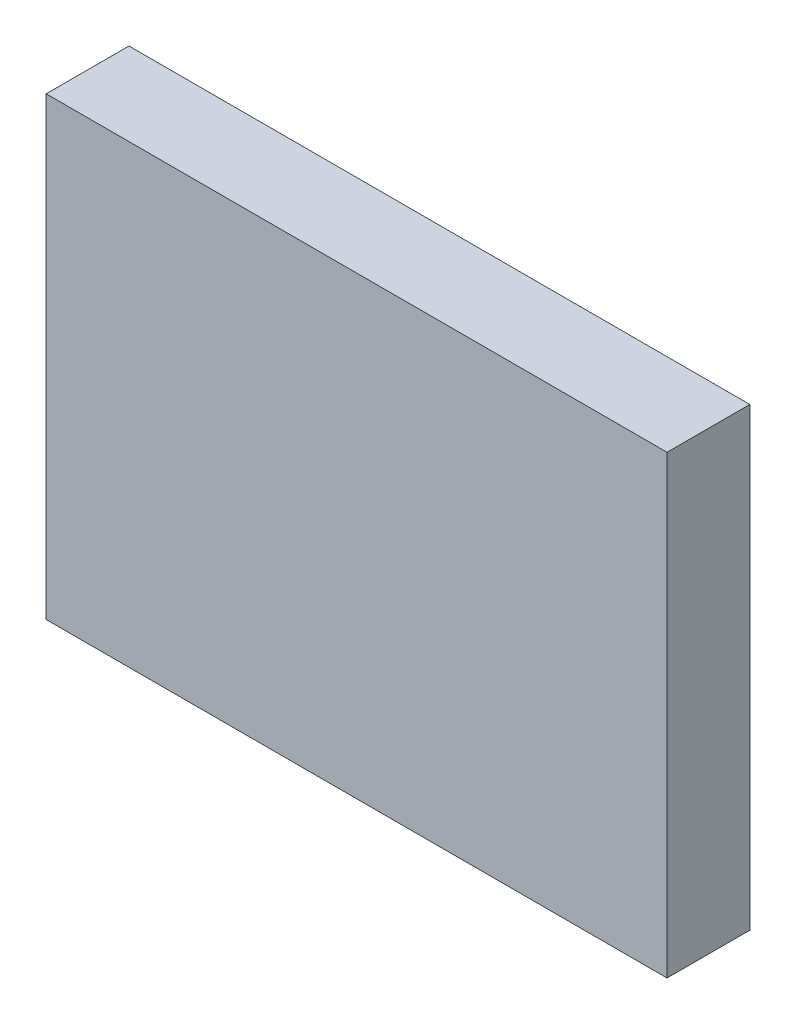
SolidWorks part; units mm, degrees
ref_plane "前视基准面" through (0, 0, 0) normal (0, 0, 1) x (1, 0, 0)
ref_plane "上视基准面" through (0, 0, 0) normal (0, 1, 0) x (1, 0, 0)
ref_plane "右视基准面" through (0, 0, 0) normal (1, 0, 0) x (0, 0, -1)
other "Configuration Table"
sketch "草图1" plane through (0, 0, 0) normal (0, 0, 1) x (1, 0, 0)
  line L1 (0, 0) -> (75, 0)
  line L2 (0, 0) -> (0, 55)
  line L3 (0, 55) -> (75, 55)
  line L4 (75, 0) -> (75, 55)
  dimension "D1" = 75
  dimension "D2" = 55
extrude "凸台-拉伸1" add sketch "草图1" along normal blind 10
